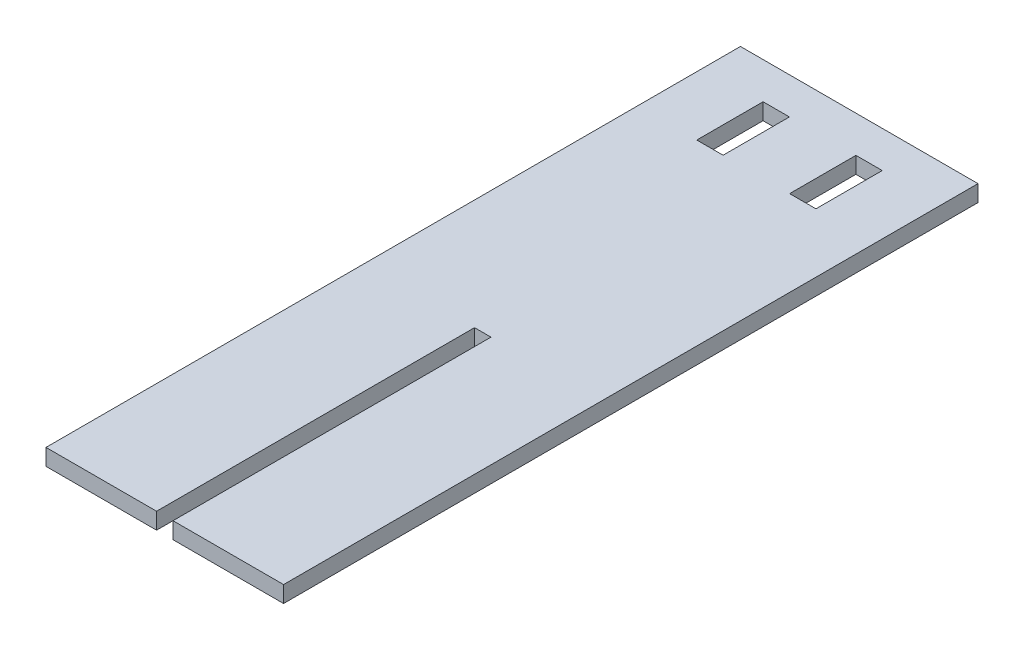
SolidWorks part; units mm, degrees
material "1.3# EPP"
ref_plane "Front Plane" through (0, 0, 0) normal (0, 0, 1) x (1, 0, 0)
ref_plane "Top Plane" through (0, 0, 0) normal (0, 1, 0) x (1, 0, 0)
ref_plane "Right Plane" through (0, 0, 0) normal (1, 0, 0) x (0, 0, -1)
sketch "Sketch1" plane through (0, 0, 0) normal (0, 1, 0) x (1, 0, 0)
  line L0 (41.275, 0) -> (41.275, 119.2876) construction
  line L1 (0, 0) -> (82.55, 0)
  line L2 (0, 0) -> (0, 241.3)
  line L3 (0, 241.3) -> (82.55, 241.3)
  line L4 (82.55, 0) -> (82.55, 241.3)
  line L5 (38.4175, 110.49) -> (44.1325, 110.49)
  line L6 (38.4175, 110.49) -> (38.4175, 0)
  line L7 (38.4175, 0) -> (44.1325, 0)
  line L8 (44.1325, 110.49) -> (44.1325, 0)
  line L13 (20.574, 228.6) -> (20.574, 205.5622)
  line L14 (52.832, 228.6) -> (61.976, 228.6)
  line L15 (52.832, 228.6) -> (52.832, 205.5622)
  line L16 (52.832, 205.5622) -> (61.976, 205.5622)
  line L17 (61.976, 228.6) -> (61.976, 205.5622)
  line L18 (29.718, 205.5622) -> (20.574, 205.5622)
  line L19 (29.718, 228.6) -> (29.718, 205.5622)
  line L20 (29.718, 228.6) -> (20.574, 228.6)
  point P5 (41.275, 0)
  point P10 (41.275, 0)
  dimension "D1" = 82.55
  dimension "D2" = 9.144
  dimension "D3" = 5.715
  dimension "D4" = 110.49
  dimension "D5" = 241.3
  dimension "D6" = 11.557
  dimension "D7" = 23.0378
  dimension "D8" = 228.6
extrude "Boss-Extrude1" add sketch "Sketch1" along normal blind 5.715
ref_plane "Center Plane" through (41.275, 0, 0) normal (-1, 0, 0) x (0, 0, 1)
equation "\"D8@Sketch1\" = \"D5@Sketch1\"-.5"
